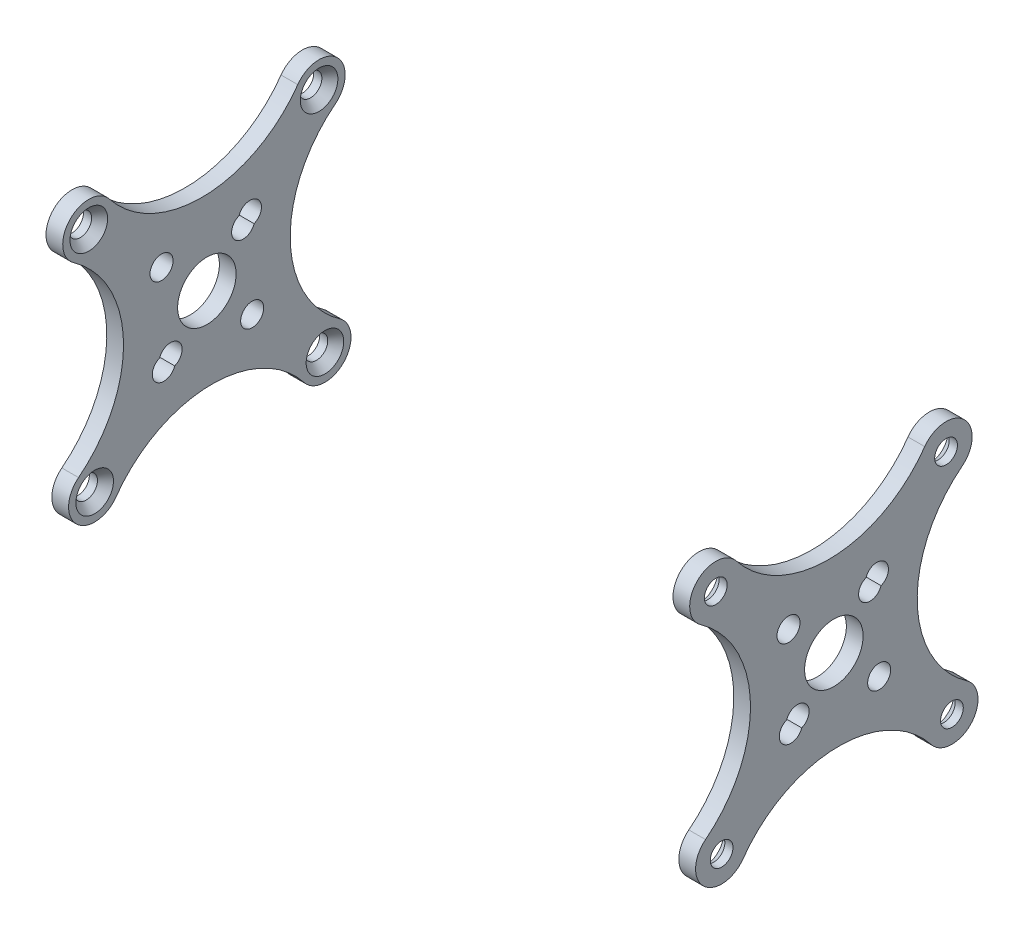
SolidWorks part; units mm, degrees
ref_plane "Front Plane" through (0, 0, 0) normal (0, 0, 1) x (1, 0, 0)
ref_plane "Top Plane" through (0, 0, 0) normal (0, 1, 0) x (1, 0, 0)
ref_plane "Right Plane" through (0, 0, 0) normal (1, 0, 0) x (0, 0, -1)
ref_plane "Plane1" through (48.9, 0, 0) normal (1, 0, 0) x (0, 0, -1)
sketch "Sketch1" plane through (48.9, 0, 0) normal (1, 0, 0) x (0, 0, -1)
  line L0 (-33.6799, -6.5169) -> (-22.6581, 5.0813) construction
  line L1 (-21.2825, -7.262) -> (-35.0554, 5.8264) construction
  circle A0 centre (-33.6799, -6.5169) radius 1.75
  circle A1 centre (-35.0554, 5.8264) radius 1.75
  circle A2 centre (-21.2825, -7.262) radius 1.75
  circle A3 centre (-22.6581, 5.0813) radius 1.75
  arc A4 (-8.6737, 14.1056) -> (-14.3577, 19.5072) centre (-11.1204, 17.2223) ccw
  arc A5 (-42.9924, 18.7775) -> (-48.394, 13.0935) centre (-46.1091, 16.3308) ccw
  arc A6 (-47.6643, -15.5412) -> (-41.9802, -20.9428) centre (-45.2175, -18.6579) ccw
  arc A7 (-13.3456, -20.2131) -> (-7.944, -14.529) centre (-10.2289, -17.7663) ccw
  circle A12 centre (-28.169, -0.7178) radius 8 construction
  circle A13 centre (-28.169, -0.7178) radius 12.675 construction
  circle A14 centre (-21.2825, -7.262) radius 3.175 construction
  circle A15 centre (-28.169, -0.7178) radius 4.445
  arc A16 (-42.9924, 18.7775) -> (-14.3577, 19.5072) centre (-28.9467, 29.8041) ccw
  arc A17 (-41.9802, -20.9428) -> (-13.3456, -20.2131) centre (-27.3912, -31.2397) cw
  arc A18 (-7.944, -14.529) -> (-8.6737, 14.1056) centre (2.3529, 0.06) cw
  arc A19 (-48.394, 13.0935) -> (-47.6643, -15.5412) centre (-58.6909, -1.4955) cw
  dimension "D1" = 3.5
  dimension "D2" = 7.9248
  dimension "D5" = 6.35
  dimension "D6" = 8.89
  dimension "D3" = 16
  dimension "D4" = 19
extrude "Boss-Extrude1" add sketch "Sketch1" against normal blind 2.54
hole_wizard "CSK for #4 Flat Head Machine Screw1" positions "Sketch2" profile "Sketch3" countersink size "#4" standard "ANSI Inch" end condition up to next
sketch "Sketch2" plane through (46.36, 0, 0) normal (-1, 0, 0) x (0, 0, 1)
  point P0 (11.1204, 17.2223)
  point P3 (46.1091, 16.3308)
  point P6 (45.2175, -18.6579)
  point P9 (10.2289, -17.7663)
sketch "Sketch3" plane through (46.36, 17.2223, 11.1204) normal (0, 1, 0) x (0, 0, 1)
  line L0 (0, 0) -> (0, 2.54)
  line L1 (0, 2.54) -> (1.7272, 2.54)
  line L2 (1.7272, 2.54) -> (1.7272, 1.3003)
  line L3 (1.7272, 1.3003) -> (2.8575, 0)
  line L5 (2.8575, 0) -> (0, 0)
  line L6 (-1.7272, 1.3003) -> (-2.8575, 0) construction
  line L11 (0, -6.35) -> (0, 107.95) construction
  dimension "Thru Hole Dia." = 3.4544
  dimension "Thru Hole Depth" = 2.54
  dimension "Near C'Sink Dia." = 5.715
  dimension "Near C'Sink Angle" = 82
sketch "Sketch4" plane through (48.9, 0, 0) normal (1, 0, 0) x (0, 0, -1)
  line L0 (-21.6248, 6.1687) -> (-34.7132, -7.6042) construction
  circle A0 centre (-28.169, -0.7178) radius 4.445 construction
  circle A1 centre (-28.169, -0.7178) radius 4.445 construction
  circle A2 centre (-34.7132, -7.6042) radius 1.75
  circle A3 centre (-21.6248, 6.1687) radius 1.75
  circle A4 centre (-22.6581, 5.0813) radius 1.75 construction
  circle A5 centre (-22.6581, 5.0813) radius 1.75 construction
  dimension "D1" = 19
  dimension "D2" = 3.5
extrude "Cut-Extrude1" cut sketch "Sketch4" against normal up to surface (2.54 mm away) up to face at (46.36, 5.0813, 20.9081)
mirror "Mirror1" about plane through (0, 0, 0) normal (1, 0, 0) of bodies 104 102
equation "\"D3@Sketch1\"=16mm"
equation "\"D4@Sketch1\"=19mm"
equation "\"D1@Sketch1\"=3.5mm"
